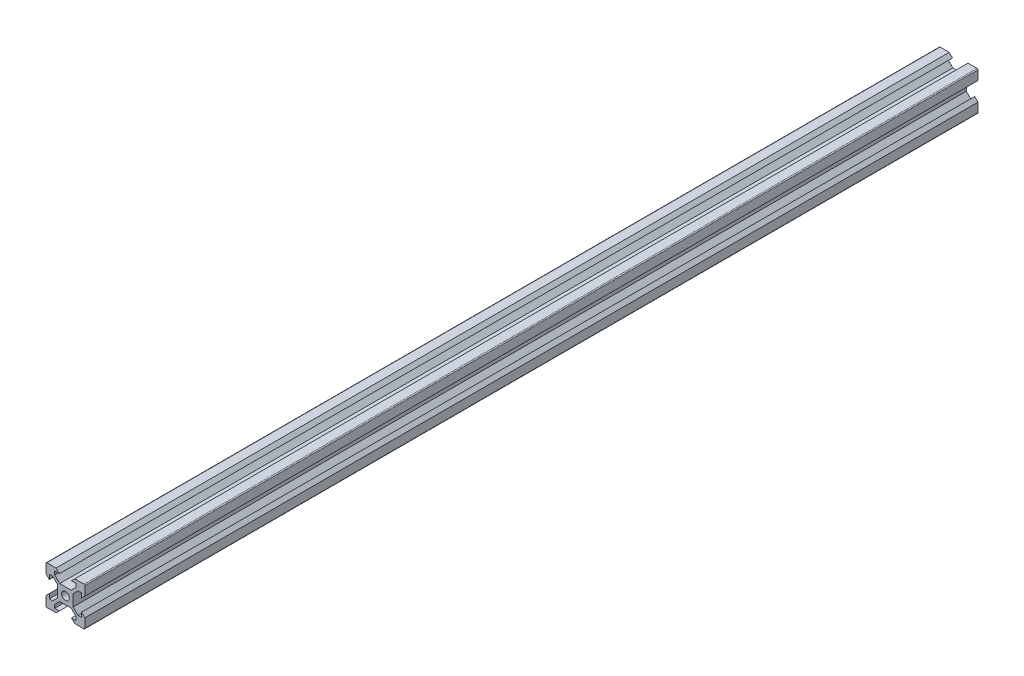
SolidWorks part; units mm, degrees
ref_plane "Alzado" through (0, 0, 0) normal (0, 0, 1) x (1, 0, 0)
ref_plane "Planta" through (0, 0, 0) normal (0, 1, 0) x (1, 0, 0)
ref_plane "Vista lateral" through (0, 0, 0) normal (1, 0, 0) x (0, 0, -1)
sketch "Croquis1" plane through (0, 0, 0) normal (0, 0, 1) x (1, 0, 0)
  line L0 (-4.825, 10) -> (-3.125, 8.3)
  line L1 (-9.5, -10) -> (-4.825, -10)
  line L2 (-10, -9.5) -> (-10, -4.825)
  line L3 (-9.5, 10) -> (-4.825, 10)
  line L4 (10, -9.5) -> (10, -4.825)
  line L5 (-10, -10) -> (10, 10) construction
  line L6 (-10, 10) -> (10, -10) construction
  line L7 (-2.9393, -4) -> (2.9393, -4)
  line L8 (-4, -2.9393) -> (-4, 2.9393)
  line L9 (-2.9393, 4) -> (2.9393, 4)
  line L10 (4, -2.9393) -> (4, 2.9393)
  line L11 (-4, -4) -> (4, 4) construction
  line L12 (-4, 4) -> (4, -4) construction
  line L13 (0, 10) -> (0, -10) construction
  line L14 (-3.125, 8.3) -> (-5.5, 8.3)
  line L15 (-6.5607, 5.5) -> (-4, 2.9393)
  line L16 (-5.5, 6.5607) -> (-2.9393, 4)
  line L17 (-9.4697, 10.5303) -> (10.5303, -9.4697) construction
  line L18 (-10, 4.825) -> (-8.3, 3.125)
  line L19 (-5.5, 8.3) -> (-5.5, 6.5607)
  line L20 (-8.3, 3.125) -> (-8.3, 5.5)
  line L21 (-8.3, 5.5) -> (-6.5607, 5.5)
  line L22 (10, 4.825) -> (8.3, 3.125)
  line L23 (8.3, 3.125) -> (8.3, 5.5)
  line L24 (8.3, 5.5) -> (6.5607, 5.5)
  line L25 (6.5607, 5.5) -> (4, 2.9393)
  line L26 (5.5, 6.5607) -> (2.9393, 4)
  line L27 (5.5, 8.3) -> (5.5, 6.5607)
  line L28 (3.125, 8.3) -> (5.5, 8.3)
  line L29 (4.825, 10) -> (3.125, 8.3)
  line L30 (4.825, -10) -> (3.125, -8.3)
  line L31 (3.125, -8.3) -> (5.5, -8.3)
  line L32 (5.5, -8.3) -> (5.5, -6.5607)
  line L33 (5.5, -6.5607) -> (2.9393, -4)
  line L34 (6.5607, -5.5) -> (4, -2.9393)
  line L35 (8.3, -5.5) -> (6.5607, -5.5)
  line L36 (8.3, -3.125) -> (8.3, -5.5)
  line L37 (10, -4.825) -> (8.3, -3.125)
  line L38 (-10, -4.825) -> (-8.3, -3.125)
  line L39 (-8.3, -3.125) -> (-8.3, -5.5)
  line L40 (-8.3, -5.5) -> (-6.5607, -5.5)
  line L41 (-6.5607, -5.5) -> (-4, -2.9393)
  line L42 (-5.5, -6.5607) -> (-2.9393, -4)
  line L43 (-5.5, -8.3) -> (-5.5, -6.5607)
  line L44 (-3.125, -8.3) -> (-5.5, -8.3)
  line L45 (-4.825, -10) -> (-3.125, -8.3)
  line L46 (-10, 4.825) -> (-10, 9.5)
  line L47 (4.825, 10) -> (9.5, 10)
  line L48 (10, 4.825) -> (10, 9.5)
  line L49 (4.825, -10) -> (9.5, -10)
  circle A0 centre (0, 0) radius 2
  arc A1 (-10, 9.5) -> (-9.5, 10) centre (-9.5, 9.5) cw
  arc A2 (9.5, 10) -> (10, 9.5) centre (9.5, 9.5) cw
  arc A3 (9.5, -10) -> (10, -9.5) centre (9.5, -9.5) ccw
  arc A4 (-9.5, -10) -> (-10, -9.5) centre (-9.5, -9.5) cw
  point P0 (0, 0)
  point P59 (0, 0)
  dimension "D2" = 4
  dimension "D9" = 0.5
  dimension "D1" = 20
  dimension "D3" = 8
  dimension "D4" = 3.125
  dimension "D5" = 5.5
  dimension "D6" = 4.3
  dimension "D7" = 4
  dimension "D8" = 0.75
extrude "Saliente-Extruir2" add sketch "Croquis1" along normal mid plane 460
